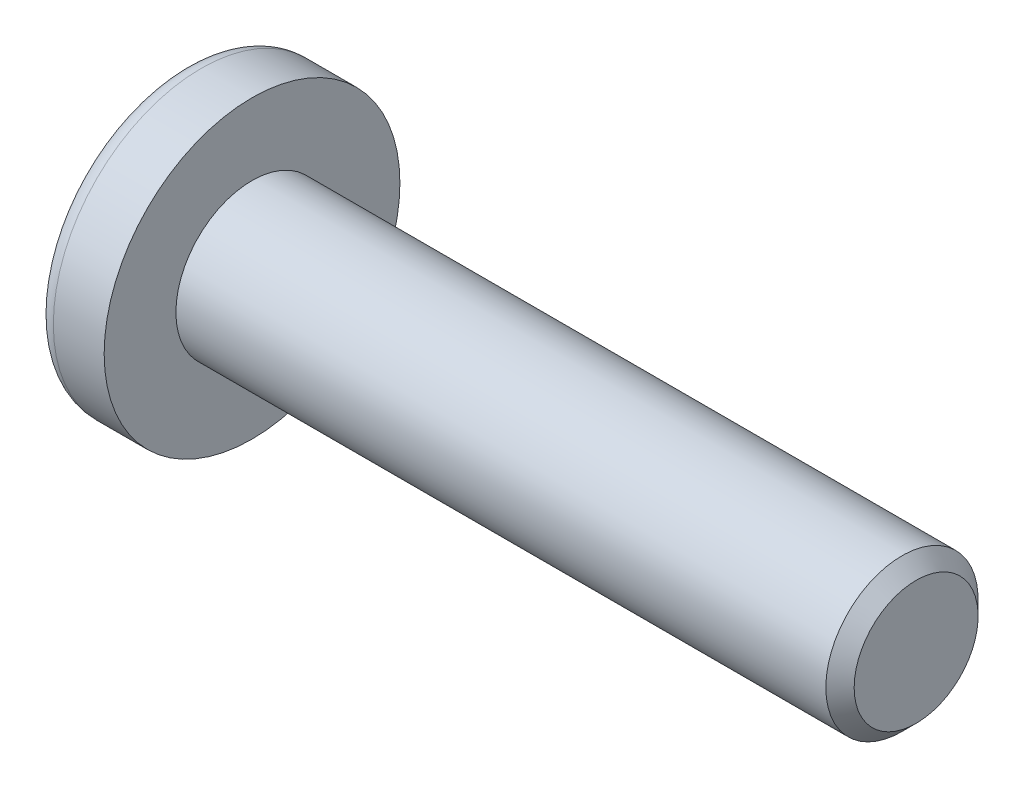
SolidWorks part; units mm, degrees
material "Alloy Steel"
ref_plane "Plane1" through (0, 0, 0) normal (0, 0, 1) x (1, 0, 0)
ref_plane "Plane2" through (0, 0, 0) normal (0, 1, 0) x (1, 0, 0)
ref_plane "Plane3" through (0, 0, 0) normal (1, 0, 0) x (0, 0, -1)
revolve "Base-Revolve" add sketch "BodySke" angle 360 about L2
sketch "BodySke" plane through (0, 0, 0) normal (0, 0, 1) x (1, 0, 0)
  line L0 (1.5748, 1.0922) -> (1.5748, 2.1209)
  line L1 (1.8021, 6.35) -> (1.8021, -3.175) construction
  line L2 (-25.4, 0) -> (127, 0) construction
  line L3 (11.0998, 0) -> (0, 0)
  line L4 (1.5748, 1.0922) -> (11.0998, 1.0922)
  line L5 (11.0998, 1.0922) -> (11.0998, 0)
  line L6 (0.8457, 2.1209) -> (1.5748, 2.1209)
  line L7 (1.5748, -1.0922) -> (11.0998, -1.0922) construction
  line L8 (1.5748, 6.35) -> (1.5748, -3.175) construction
  arc A0 (0.6381, 2.0132) -> (0, 0) centre (3.495, 0) ccw
  arc A2 (0.6381, 2.0132) -> (0.8457, 2.1209) centre (0.8457, 1.8669) cw
  dimension "Head_fillet_rad" = 0.254
  dimension "Head_crown_rad" = 3.495
  dimension "Head_ht" = 1.5748
  dimension "Diameter" = 2.1844
  dimension "Length" = 9.525
  dimension "Head_dia" = 4.2418
  dimension "Advance" = 0.4547
  dimension "Thread_nom" = 9.525
cosmetic thread "ThreadCosmetic" parameters "Thread_length"=9.0703, "Thread_minor"=1.6459
sketch "Sketch3" plane through (0, 0, 0) normal (1, 0, 0) x (0, 0, -1)
  line L0 (0.3429, -1.3843) -> (-0.3429, -1.3843)
  line L1 (0.3429, -1.3843) -> (0.3429, 1.3843)
  line L2 (-0.3429, 1.3843) -> (0.3429, 1.3843)
  line L3 (-0.3429, 1.3843) -> (-0.3429, -1.3843)
  dimension "D1" = 1.3843
  dimension "Cross_dia" = 2.7686
  dimension "D2" = 0.3429
  dimension "Cross_width" = 0.6858
ref_plane "Plane4" through (1.4986, 0, 0) normal (1, 0, 0) x (0, 0, -1)
sketch "Sketch4" plane through (1.4986, 0, 0) normal (1, 0, 0) x (0, 0, -1)
  line L0 (0.1714, -0.1715) -> (-0.1714, -0.1715)
  line L1 (0.1714, -0.1715) -> (0.1714, 0.1714)
  line L2 (-0.1714, 0.1714) -> (0.1714, 0.1714)
  line L3 (-0.1714, 0.1714) -> (-0.1714, -0.1715)
  dimension "D1" = 0.3429
  dimension "D2" = 0.3429
  dimension "D3" = 0.1714
  dimension "D4" = 0.1714
loft "Cut-Loft1" cut profiles "Sketch3", "Sketch4"
pattern_circular "CirPattern1" count 2 every 90 about axis through (0, 0, 0) along (1, 0, 0) of "Cut-Loft1"
chamfer "Chamfer1" distance 0.2032 angle 45 1 edges at (11.0998, 0, 1.0922)
equation "\"D1@Sketch3\" = \"Cross_dia@Sketch3\" / 2"
equation "\"D2@Sketch3\" = \"Cross_width@Sketch3\" / 2"
equation "\"D1@Sketch4\" = \"Cross_width@Sketch3\" *.5"
equation "\"D2@Sketch4\" = \"D1@Sketch4\""
equation "\"D3@Sketch4\" = \"D1@Sketch4\" / 2"
equation "\"D4@Sketch4\" = \"D2@Sketch4\" / 2"
equation "\"Thread_length@ThreadCosmetic\" = ((sgn( (\"Length@BodySke\" - \"Advance@BodySke\" ) - \"Thread_nom@BodySke\" )-1)*( (\"Length@BodySke\" - \"Advance@BodySke\" ) - \"Thread_nom@BodySke\" ))/-2+ \"Thread_nom@BodySke\""
